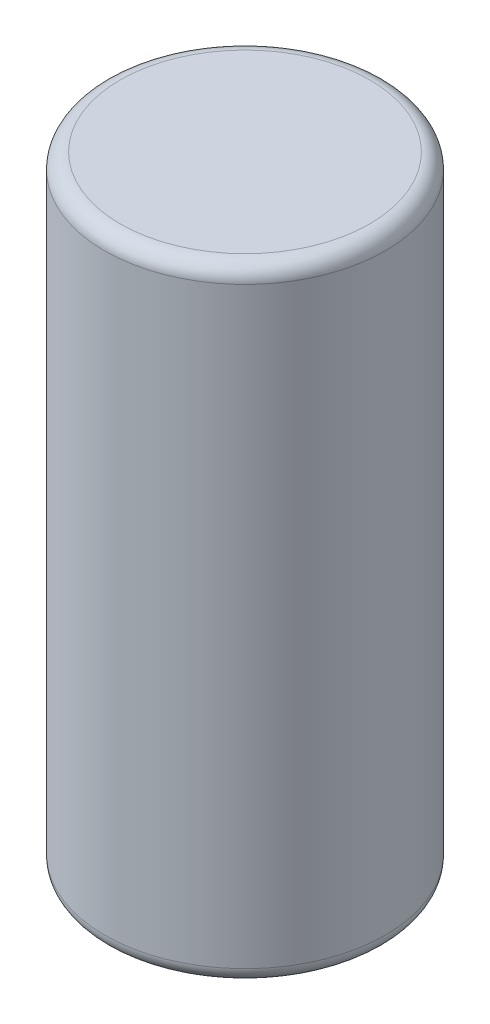
SolidWorks part; units mm, degrees
ref_plane "Front Plane" through (0, 0, 0) normal (0, 0, 1) x (1, 0, 0)
ref_plane "Top Plane" through (0, 0, 0) normal (0, 1, 0) x (1, 0, 0)
ref_plane "Right Plane" through (0, 0, 0) normal (1, 0, 0) x (0, 0, -1)
sketch "Sketch2" plane through (0, 0, 0) normal (0, 1, 0) x (1, 0, 0)
  circle A0 centre (0, 0) radius 9
  dimension "D1" = 18
extrude "Boss-Extrude1" add sketch "Sketch2" along normal blind 40
sketch "Sketch4" plane through (0, 0, 0) normal (0, -1, 0) x (1, 0, 0)
  line L0 (-2.8677, 0.8812) -> (2.8677, 0.8812)
  arc A0 (-2.8677, 0.8812) -> (2.8677, 0.8812) centre (0, 0) ccw
  dimension "D1" = 6
  dimension "D2" = 0.8812
extrude "Cut-Extrude1" cut sketch "Sketch4" against normal blind 10
fillet "Fillet1" radius 1 1 edges at (0, 0, 9)
fillet "Fillet2" radius 1 1 edges at (0, 40, 9)
